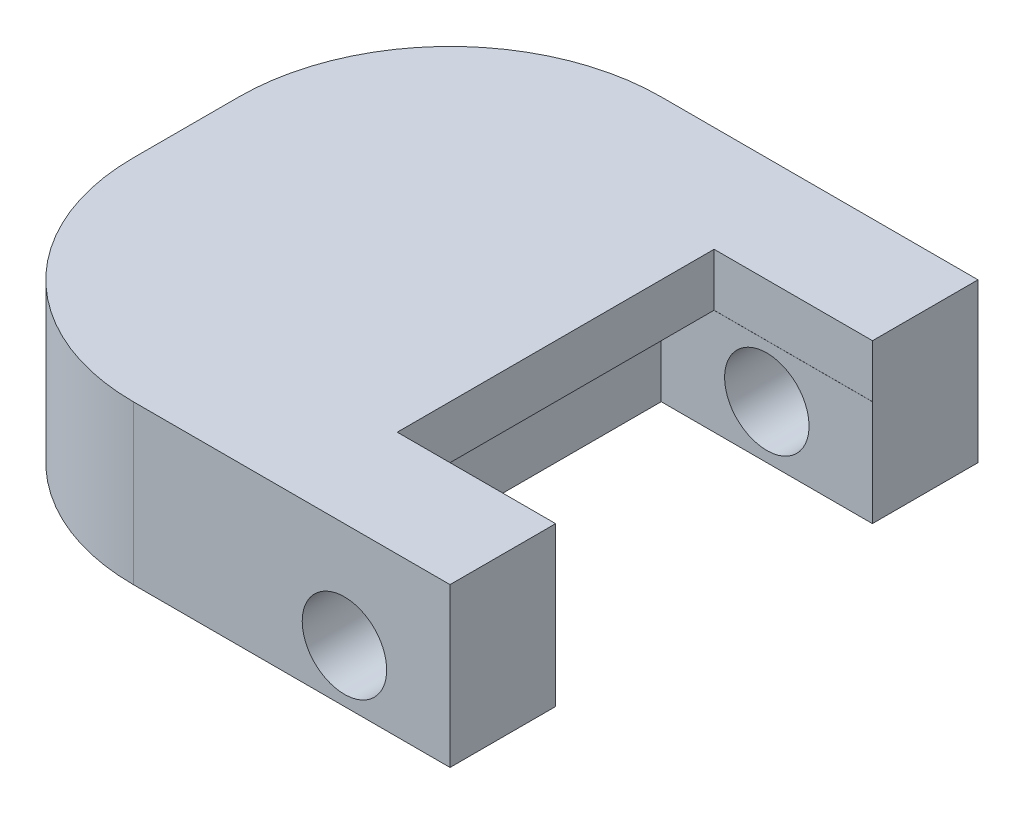
SolidWorks part; units mm, degrees
material "Plain Carbon Steel"
ref_plane "Front Plane" through (0, 0, 0) normal (0, 0, 1) x (1, 0, 0)
ref_plane "Top Plane" through (0, 0, 0) normal (0, 1, 0) x (1, 0, 0)
ref_plane "Right Plane" through (0, 0, 0) normal (1, 0, 0) x (0, 0, -1)
sketch "Sketch1" plane through (0, 0, 0) normal (0, 1, 0) x (1, 0, 0)
  line L1 (63.5, 63.5) -> (-12.7, 63.5)
  line L2 (63.5, 63.5) -> (63.5, -63.5)
  line L3 (63.5, -63.5) -> (-12.7, -63.5)
  line L4 (-63.5, 12.7) -> (-63.5, -12.7)
  line L5 (63.5, 63.5) -> (-63.5, -63.5) construction
  line L6 (63.5, -63.5) -> (-63.5, 63.5) construction
  arc A0 (-12.7, -63.5) -> (-63.5, -12.7) centre (-12.7, -12.7) cw
  arc A1 (-12.7, 63.5) -> (-63.5, 12.7) centre (-12.7, 12.7) ccw
  point P0 (0, 0)
  dimension "D2" = 50.8
  dimension "D1" = 127
  dimension "4" = 127
extrude "Boss-Extrude1" add sketch "Sketch1" along normal blind 38.1
sketch "Sketch2" plane through (63.5, 0, 0) normal (1, 0, 0) x (0, 0, -1)
  line L0 (-63.5, 38.1) -> (63.5, 38.1) construction
  line L1 (-38.1, 25.4) -> (38.1, 25.4)
  line L2 (-38.1, 25.4) -> (-38.1, -25.4)
  line L3 (-38.1, -25.4) -> (38.1, -25.4)
  line L4 (38.1, 25.4) -> (38.1, -25.4)
  line L5 (-38.1, 25.4) -> (38.1, -25.4) construction
  line L6 (-38.1, -25.4) -> (38.1, 25.4) construction
  point P0 (0, 0)
  dimension "D1" = 76.2
  dimension "D2" = 12.7
extrude "Cut-Extrude1" cut sketch "Sketch2" against normal blind 50.8
sketch "Sketch3" plane through (0, 0, 38.1) normal (0, 0, -1) x (-1, 0, 0)
  line L2 (-12.7, 25.4) -> (-63.5, 25.4) construction
  line L3 (-63.5, 38.1) -> (-63.5, 0) construction
  circle A1 centre (-38.1, 12.7) radius 10.16
  dimension "D3" = 20.32
  dimension "D1" = 12.7
  dimension "D2" = 25.4
extrude "Cut-Extrude2" cut sketch "Sketch3" against normal through all and the other way through all
ref_plane "Plane1" through (63.5, 38.1, -63.5) normal (0, 0, -1) x (-1, 0, 0)
sketch "Sketch6" plane through (63.5, 0, 0) normal (1, 0, 0) x (0, 0, -1)
  line L0 (-63.5, 38.1) -> (63.5, 38.1) construction
  line L1 (-38.1, 25.4) -> (38.1232, 25.4)
  line L2 (-38.1, 25.4) -> (-38.1, 38.1)
  line L3 (-38.1, 38.1) -> (38.1232, 38.1)
  line L4 (38.1232, 25.4) -> (38.1232, 38.1)
extrude "Cut-Extrude4" cut sketch "Sketch6" against normal blind 38.1
